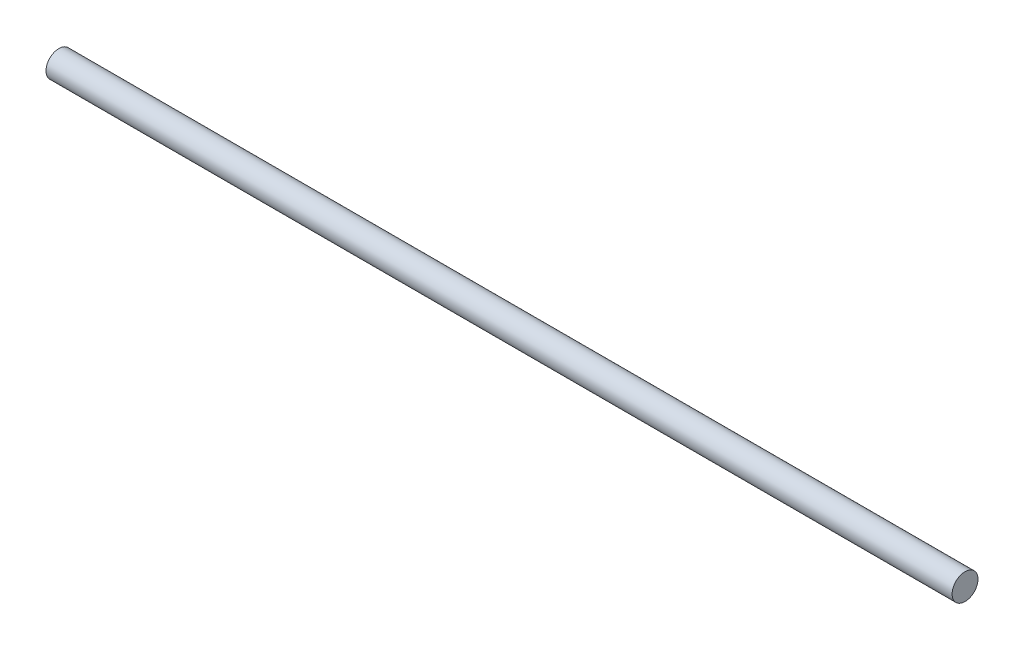
SolidWorks part; units mm, degrees
ref_plane "Front Plane" through (0, 0, 0) normal (0, 0, 1) x (1, 0, 0)
ref_plane "Top Plane" through (0, 0, 0) normal (0, 1, 0) x (1, 0, 0)
ref_plane "Right Plane" through (0, 0, 0) normal (1, 0, 0) x (0, 0, -1)
sketch "Sketch1" plane through (0, 0, 0) normal (1, 0, 0) x (0, 0, -1)
  circle A0 centre (0, 0) radius 1
  dimension "D1" = 2
extrude "Rod" add sketch "Sketch1" along normal mid plane 70
